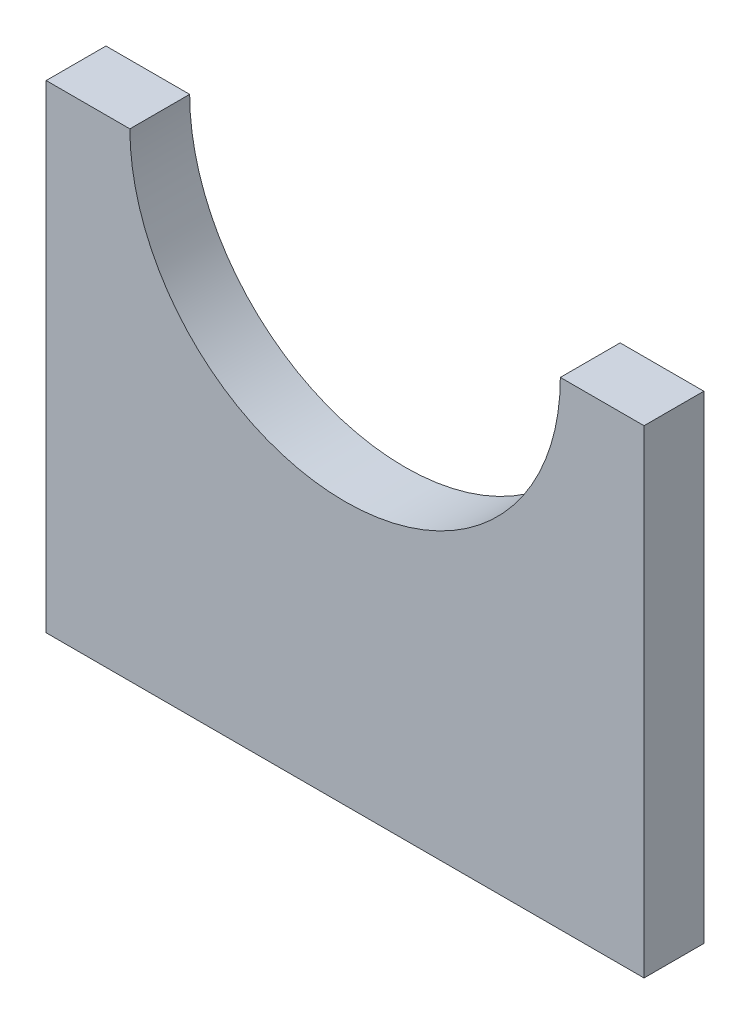
SolidWorks part; units mm, degrees
ref_plane "Front Plane" through (0, 0, 0) normal (0, 0, 1) x (1, 0, 0)
ref_plane "Top Plane" through (0, 0, 0) normal (0, 1, 0) x (1, 0, 0)
ref_plane "Right Plane" through (0, 0, 0) normal (1, 0, 0) x (0, 0, -1)
sketch "Sketch1" plane through (0, 0, 0) normal (0, 0, 1) x (1, 0, 0)
  line L0 (-44.7164, 0) -> (54.8723, 0) construction
  line L1 (-25, 0) -> (-25, -40)
  line L2 (-25, -40) -> (25, -40)
  line L3 (25, -40) -> (25, 0)
  line L4 (0, -24.725) -> (0, -64.725) construction
  line L5 (-25, 0) -> (-18, 0)
  line L6 (18, 0) -> (25, 0)
  arc A0 (-18, 0) -> (18, 0) centre (0, 0) ccw
  point P7 (-35, 0)
  point P8 (35, 0)
  dimension "D1" = 36
  dimension "D3" = 40
  dimension "D2" = 25
extrude "Boss-Extrude1" add sketch "Sketch1" along normal mid plane 5
